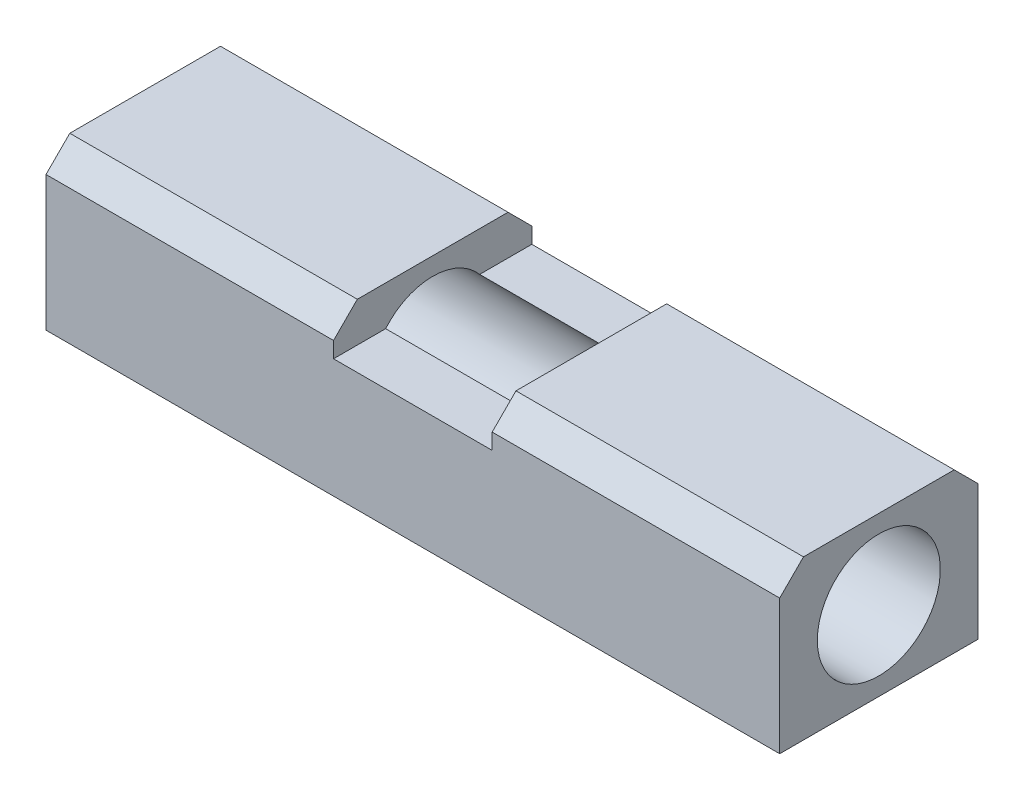
SolidWorks part; units mm, degrees
material "3.1655 (EN AW-2011)"
ref_plane "Plan de face" through (0, 0, 0) normal (0, 0, 1) x (1, 0, 0)
ref_plane "Plan de dessus" through (0, 0, 0) normal (0, 1, 0) x (1, 0, 0)
ref_plane "Plan de droite" through (0, 0, 0) normal (1, 0, 0) x (0, 0, -1)
sketch "Esquisse1" plane through (0, 0, 0) normal (0, 0, 1) x (1, 0, 0)
  line L1 (0, 0) -> (185, 0)
  line L2 (0, 0) -> (0, 40)
  line L3 (0, 40) -> (185, 40)
  line L4 (185, 0) -> (185, 40)
  dimension "D1" = 185
  dimension "D2" = 40
extrude "Boss.-Extru.1" add sketch "Esquisse1" along normal blind 50
sketch "Esquisse2" plane through (0, 0, 0) normal (-1, 0, 0) x (0, 0, 1)
  line L0 (50, 40) -> (50, 0) construction
  line L1 (50, 40) -> (0, 40) construction
  circle A0 centre (25, 20) radius 15.5092
  dimension "D2" = 20
  dimension "D1" = 25
extrude "Enlèv. mat.-Extru.1" cut sketch "Esquisse2" against normal blind 185
chamfer "Chanfrein1" distance 6 angle 45 2 edges at (92.5, 40, 50) (92.5, 40, 0)
sketch "Esquisse3" plane through (0, 0, 0) normal (0, -1, 0) x (1, 0, 0)
  line L0 (92.5, 50) -> (92.5, 0) construction
  line L1 (0, 50) -> (185, 50) construction
  line L2 (0, 0) -> (185, 0) construction
  line L3 (0, 25) -> (185, 25) construction
  line L4 (0, 50) -> (0, 0) construction
  line L5 (185, 50) -> (185, 0) construction
  circle A0 centre (6, 44) radius 2
  circle A1 centre (6, 6) radius 2
  circle A2 centre (179, 6) radius 2
  circle A3 centre (179, 44) radius 2
  point P16 (7.6779, 50)
  dimension "D1" = 4
  dimension "D2" = 6
  dimension "D3" = 6
extrude "Enlèv. mat.-Extru.2" cut sketch "Esquisse3" against normal blind 15
sketch "Esquisse4" plane through (0, 0, 50) normal (0, 0, 1) x (1, 0, 0)
  line L0 (0, 40) -> (185, 40) construction
  line L1 (72.5, 40) -> (112.5, 40)
  line L2 (72.5, 40) -> (72.5, 30)
  line L3 (72.5, 30) -> (112.5, 30)
  line L4 (112.5, 40) -> (112.5, 30)
  line L5 (0, 34) -> (0, 0) construction
  dimension "D1" = 40
  dimension "D2" = 72.5
  dimension "D3" = 10
extrude "Enlèv. mat.-Extru.3" cut sketch "Esquisse4" against normal blind 50
